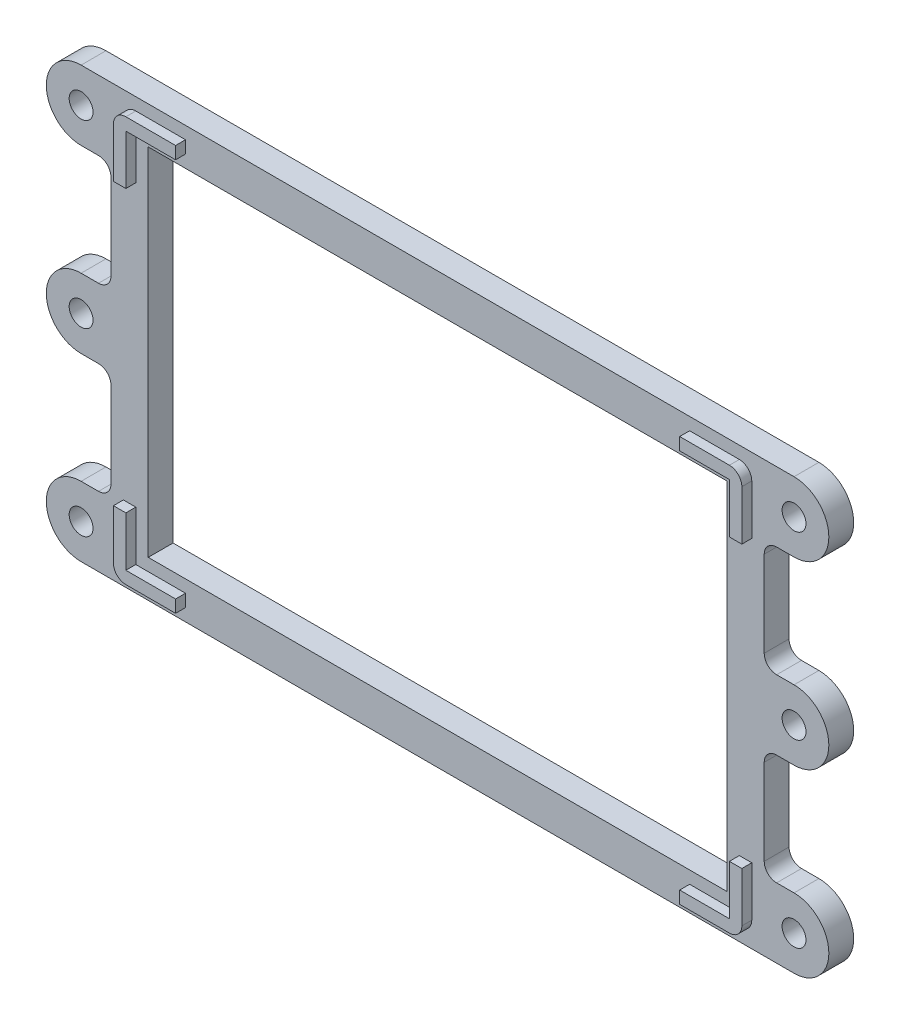
SolidWorks part; units mm, degrees
ref_plane "Front Plane" through (0, 0, 0) normal (0, 0, 1) x (1, 0, 0)
ref_plane "Top Plane" through (0, 0, 0) normal (0, 1, 0) x (1, 0, 0)
ref_plane "Right Plane" through (0, 0, 0) normal (1, 0, 0) x (0, 0, -1)
sketch "Sketch1" plane through (0, 0, 0) normal (0, 0, 1) x (1, 0, 0)
  line L0 (0, 37.9) -> (0, -37.9) construction
  line L1 (-60.35, 37.9) -> (60.35, 37.9) construction
  line L2 (-60.35, 37.9) -> (-60.35, -37.9) construction
  line L3 (-60.35, -37.9) -> (0, -37.9) construction
  line L4 (60.35, 37.9) -> (60.35, -37.9) construction
  line L5 (-60.35, 37.9) -> (60.35, -37.9) construction
  line L6 (-60.35, -37.9) -> (60.35, 37.9) construction
  line L7 (-60.35, 0) -> (60.35, 0) construction
  line L8 (-60.7, 38.25) -> (-60.7, 28.25)
  line L9 (-60.7, -38.25) -> (-50.7, -38.25)
  line L10 (-50.7, -38.25) -> (-50.7, -40.75)
  line L11 (-60.7, -28.25) -> (-63.2, -28.25)
  line L12 (-63.2, -28.25) -> (-63.2, -38.25)
  line L13 (-60.7, -40.75) -> (-50.7, -40.75)
  line L14 (60.7, 38.25) -> (60.7, 28.25)
  line L15 (-60.7, 38.25) -> (-50.7, 38.25)
  line L16 (-50.7, 38.25) -> (-50.7, 40.75)
  line L17 (-60.7, 40.75) -> (-50.7, 40.75)
  line L18 (-63.2, 28.25) -> (-63.2, 38.25)
  line L19 (-60.7, 28.25) -> (-63.2, 28.25)
  line L20 (50.7, -38.25) -> (50.7, -40.75)
  line L21 (60.7, -28.25) -> (63.2, -28.25)
  line L22 (63.2, -28.25) -> (63.2, -38.25)
  line L23 (60.7, -40.75) -> (50.7, -40.75)
  line L24 (60.7, 28.25) -> (63.2, 28.25)
  line L25 (50.7, 38.25) -> (50.7, 40.75)
  line L26 (60.7, 40.75) -> (50.7, 40.75)
  line L27 (63.2, 28.25) -> (63.2, 38.25)
  line L28 (-60.35, 37.9) -> (-60.35, -37.9) construction
  line L29 (-60.7, 28.25) -> (-60.7, -28.25) construction
  line L30 (-60.7, -28.25) -> (-60.7, -38.25)
  line L31 (-60.7, 38.25) -> (-60.7, -38.25) construction
  line L32 (-50.7, 38.25) -> (50.7, 38.25) construction
  line L33 (50.7, 38.25) -> (60.7, 38.25)
  line L34 (-60.7, 38.25) -> (60.7, 38.25) construction
  line L35 (60.7, 28.25) -> (60.7, -28.25) construction
  line L36 (60.7, -28.25) -> (60.7, -38.25)
  line L37 (60.7, 38.25) -> (60.7, -38.25) construction
  line L38 (-50.7, -38.25) -> (50.7, -38.25) construction
  line L39 (50.7, -38.25) -> (60.7, -38.25)
  line L40 (-60.7, -38.25) -> (60.7, -38.25) construction
  line L41 (0, -37.9) -> (60.35, -37.9) construction
  line L42 (-60.35, -37.9) -> (60.35, -37.9) construction
  arc A0 (-63.2, -38.25) -> (-60.7, -40.75) centre (-60.7, -38.25) ccw
  arc A1 (-63.2, 38.25) -> (-60.7, 40.75) centre (-60.7, 38.25) cw
  arc A2 (63.2, -38.25) -> (60.7, -40.75) centre (60.7, -38.25) cw
  arc A3 (63.2, 38.25) -> (60.7, 40.75) centre (60.7, 38.25) ccw
  point P0 (0, 0)
  point P17 (-64.537, -41.0531)
  point P22 (0, 0)
  point P23 (0, 0)
  point P30 (-70.4249, -40.3827)
  dimension "D8" = 2.5
  dimension "D1" = 120.7
  dimension "D2" = 75.8
  dimension "D4" = 10
  dimension "D5" = 10
  dimension "D6" = 2.5
  dimension "D7" = 2.5
  dimension "D3" = 0.35
extrude "Boss-Extrude3" add sketch "Sketch1" against normal blind 2 contours A2 L22 L21 L36 L39 L20 L23 | L27 A3 L26 L25 L33 L14 L24 | A1 L18 L19 L8 L15 L16 L17 | L12 A0 L13 L10 L9 L30 L11
sketch "Sketch2" plane through (0, 0, -2) normal (0, 0, -1) x (-1, 0, 0)
  line L0 (-50.7, 38.25) -> (-60.7, 38.25) construction
  line L1 (-65.7, 43.25) -> (65.7, 43.25)
  line L2 (-65.7, 43.25) -> (-65.7, -43.25)
  line L3 (-65.7, -43.25) -> (65.7, -43.25)
  line L4 (65.7, 43.25) -> (65.7, -43.25)
  line L5 (-65.7, 43.25) -> (65.7, -43.25) construction
  line L6 (-65.7, -43.25) -> (65.7, 43.25) construction
  line L7 (-60.7, 40.75) -> (-50.7, 40.75) construction
  line L8 (-63.2, 28.25) -> (-63.2, 38.25) construction
  line L9 (0, 43.25) -> (0, -43.25) construction
  line L10 (-65.7, 0) -> (65.7, 0) construction
  line L11 (-65.7, 0) -> (-71.7, 0) construction
  line L12 (-65.7, -7) -> (-71.7, -7)
  line L13 (-65.7, 7) -> (-71.7, 7)
  line L14 (58.2, -35.75) -> (-58.2, -35.75)
  line L15 (58.2, -35.75) -> (58.2, 35.75)
  line L16 (58.2, 35.75) -> (-58.2, 35.75)
  line L17 (-58.2, -35.75) -> (-58.2, 35.75)
  line L18 (58.2, -35.75) -> (-58.2, 35.75) construction
  line L19 (58.2, 35.75) -> (-58.2, -35.75) construction
  line L20 (-60.7, 38.25) -> (-60.7, 28.25) construction
  line L21 (-65.7, -43.25) -> (-71.7, -43.25)
  line L22 (-65.7, -29.25) -> (-71.7, -29.25)
  line L23 (-65.7, 29.25) -> (-71.7, 29.25)
  line L24 (-65.7, 43.25) -> (-71.7, 43.25)
  line L25 (-71.7, 43.25) -> (-65.7, 43.25)
  line L26 (-71.7, -43.25) -> (-65.7, -43.25)
  line L27 (65.7, 43.25) -> (71.7, 43.25)
  line L28 (65.7, 29.25) -> (71.7, 29.25)
  line L29 (65.7, 7) -> (71.7, 7)
  line L30 (65.7, -7) -> (71.7, -7)
  line L31 (65.7, -43.25) -> (71.7, -43.25)
  line L32 (65.7, -29.25) -> (71.7, -29.25)
  arc A1 (-71.7, 7) -> (-71.7, -7) centre (-71.7, 0) ccw
  circle A2 centre (-71.7, 0) radius 2.4
  arc A3 (-71.7, -29.25) -> (-71.7, -43.25) centre (-71.7, -36.25) ccw
  circle A4 centre (-71.7, -36.25) radius 2.4
  circle A5 centre (-71.7, 36.25) radius 2.4
  arc A6 (-71.7, 29.25) -> (-71.7, 43.25) centre (-71.7, 36.25) cw
  arc A7 (71.7, 29.25) -> (71.7, 43.25) centre (71.7, 36.25) ccw
  circle A8 centre (71.7, 36.25) radius 2.4
  circle A9 centre (71.7, -36.25) radius 2.4
  arc A10 (71.7, -29.25) -> (71.7, -43.25) centre (71.7, -36.25) cw
  circle A11 centre (71.7, 0) radius 2.4
  arc A12 (71.7, 7) -> (71.7, -7) centre (71.7, 0) cw
  point P0 (0, 0)
  point P26 (0, 0)
  line M22 (-63.2, 38.25) -> (-63.2, 28.25)
  line M23 (-63.2, 28.25) -> (-60.7, 28.25)
  line M24 (-60.7, 28.25) -> (-60.7, 38.25)
  line M25 (-60.7, 38.25) -> (-50.7, 38.25)
  line M26 (-50.7, 38.25) -> (-50.7, 40.75)
  line M27 (-50.7, 40.75) -> (-60.7, 40.75)
  arc M28 (-60.7, 40.75) -> (-63.2, 38.25) centre (-60.7, 38.25) ccw
  dimension "D3" = 7
  dimension "D4" = 4.8
  dimension "D8" = 7
  dimension "D10" = 4.8
  dimension "D1" = 2.5
  dimension "D2" = 2.5
  dimension "D5" = 6
  dimension "D6" = 2.5
  dimension "D7" = 2.5
  dimension "D9" = 6
extrude "Boss-Extrude4" add sketch "Sketch2" along normal blind 5 contours L4 L1 L2 L3 L14 L17 L16 L15 M22 M28 M27 M26 M25 M24 M23 | A6 L23 L2 L24 A5 | L13 A1 L12 L2 A2 | L22 A3 L21 L2 A4 | L28 A7 L27 L4 A8 | A12 L29 L4 L30 A11 | A10 L32 L4 L31 A9 | M28 M22 M23 M24 M25 M26 M27
fillet "Fillet1" radius 2.5 8 edges at (-65.7, 29.25, -4.5) (-65.7, 7, -4.5) (-65.7, -29.25, -4.5) (-65.7, -7, -4.5) (65.7, -29.25, -4.5) (65.7, -7, -4.5) (65.7, 7, -4.5) (65.7, 29.25, -4.5)
